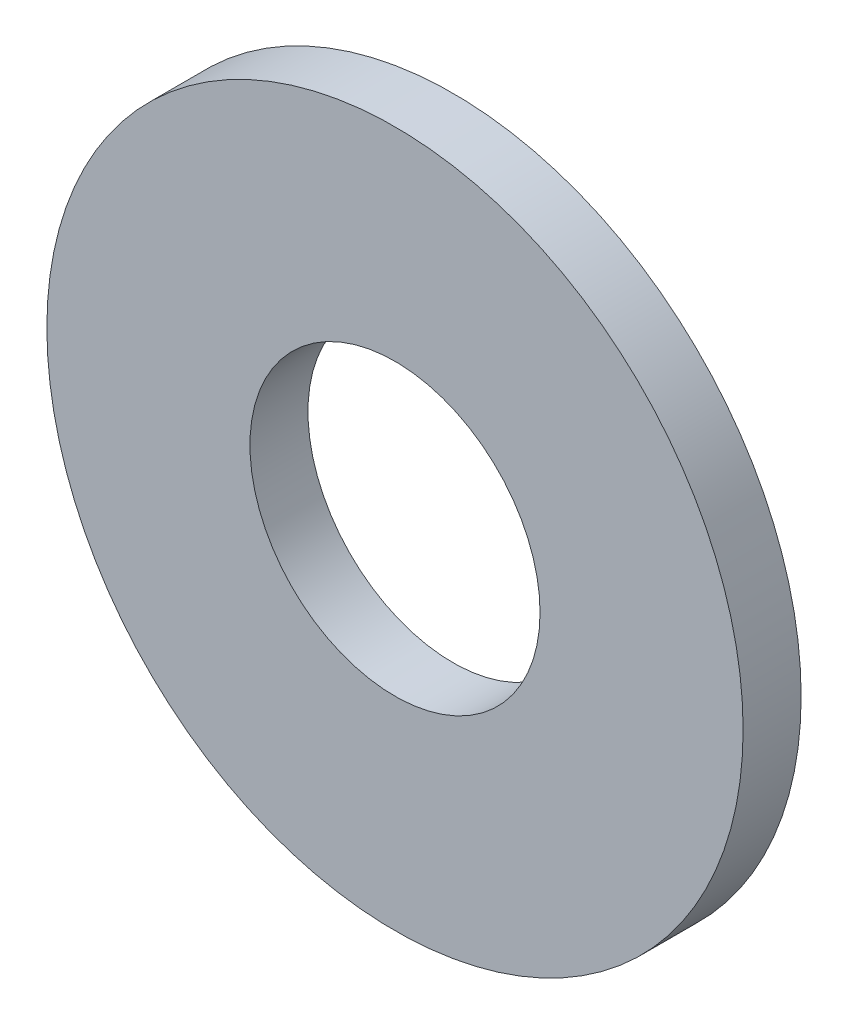
SolidWorks part; units mm, degrees
ref_plane "Front Plane" through (0, 0, 0) normal (0, 0, 1) x (1, 0, 0)
ref_plane "Top Plane" through (0, 0, 0) normal (0, 1, 0) x (1, 0, 0)
ref_plane "Right Plane" through (0, 0, 0) normal (1, 0, 0) x (0, 0, -1)
sketch "Sketch1" plane through (0, 0, 0) normal (0, 0, 1) x (1, 0, 0)
  circle A0 centre (0, 0) radius 9.525
  circle A1 centre (0, 0) radius 3.9688
  dimension "D1" = 7.9375
  dimension "D2" = 19.05
extrude "Boss-Extrude1" add sketch "Sketch1" along normal mid plane 1.5875
